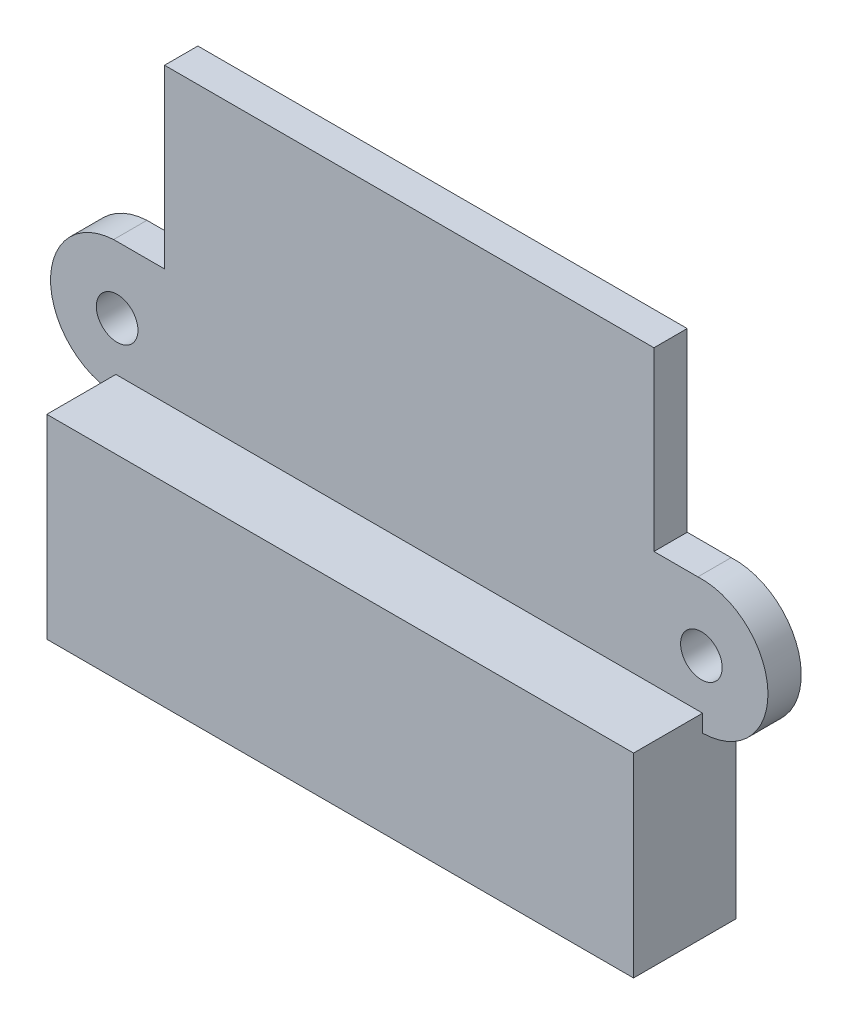
SolidWorks part; units mm, degrees
ref_plane "Front Plane" through (0, 0, 0) normal (0, 0, 1) x (1, 0, 0)
ref_plane "Top Plane" through (0, 0, 0) normal (0, 1, 0) x (1, 0, 0)
ref_plane "Right Plane" through (0, 0, 0) normal (1, 0, 0) x (0, 0, -1)
sketch "Sketch1" plane through (0, 0, 0) normal (0, 0, 1) x (1, 0, 0)
  line L0 (0, 7.4306) -> (0, -7.4306) construction
  line L1 (-7.4676, 7.4306) -> (7.4676, 7.4306)
  line L2 (-7.4676, 7.4306) -> (-7.4676, 2.0458)
  line L3 (-8.9535, -7.4306) -> (8.9535, -7.4306)
  line L4 (7.4676, 7.4306) -> (7.4676, 2.0458)
  line L5 (8.9535, -2.0151) -> (8.9535, -7.4306)
  line L6 (7.4676, 2.0458) -> (8.8086, 2.0458)
  line L7 (-8.9535, -2.0151) -> (-8.9535, -7.4306)
  line L10 (-7.4676, 2.0458) -> (-9.0222, 2.0458)
  arc A0 (8.9535, -2.0151) -> (8.8086, 2.0458) centre (8.9154, 0.0166) ccw
  arc A1 (-9.0222, 2.0458) -> (-8.9535, -2.0151) centre (-8.9154, 0.0166) ccw
  circle A2 centre (-8.9154, 0.0166) radius 0.635
  circle A3 centre (8.9154, 0.0166) radius 0.635
  dimension "D7" = 17.8308
  dimension "D9" = 2.032
  dimension "D10" = 2.032
  dimension "D12" = 1.27
  dimension "D13" = 1.27
  dimension "D4" = 7.4471
  dimension "D1" = 14.9352
  dimension "D2" = 14.9352
  dimension "D3" = 5.3848
  dimension "D5" = 5.3848
  dimension "D8" = 1.4478
  dimension "D11" = 1.4478
  dimension "D14" = 17.907
extrude "Boss-Extrude1" add sketch "Sketch1" along normal blind 1.016 contours L4 L6 A0 L5 L3 L7 A1 L10 L2 L1 | A2 | A3
sketch "Sketch2" plane through (0, 0, 1.016) normal (0, 0, 1) x (1, 0, 0)
  line L0 (8.9535, -2.0151) -> (8.9535, -7.4306) construction
  line L1 (-8.9535, -7.4306) -> (8.9535, -7.4306)
  line L2 (-8.9535, -7.4306) -> (-8.9535, -1.4848)
  line L3 (-8.9535, -1.4848) -> (8.9535, -1.4848)
  line L4 (8.9535, -7.4306) -> (8.9535, -1.4848)
  line L5 (-7.4676, 7.4306) -> (7.4676, 7.4306) construction
  dimension "D1" = 8.9154
extrude "Boss-Extrude2" add sketch "Sketch2" along normal blind 2.1082
